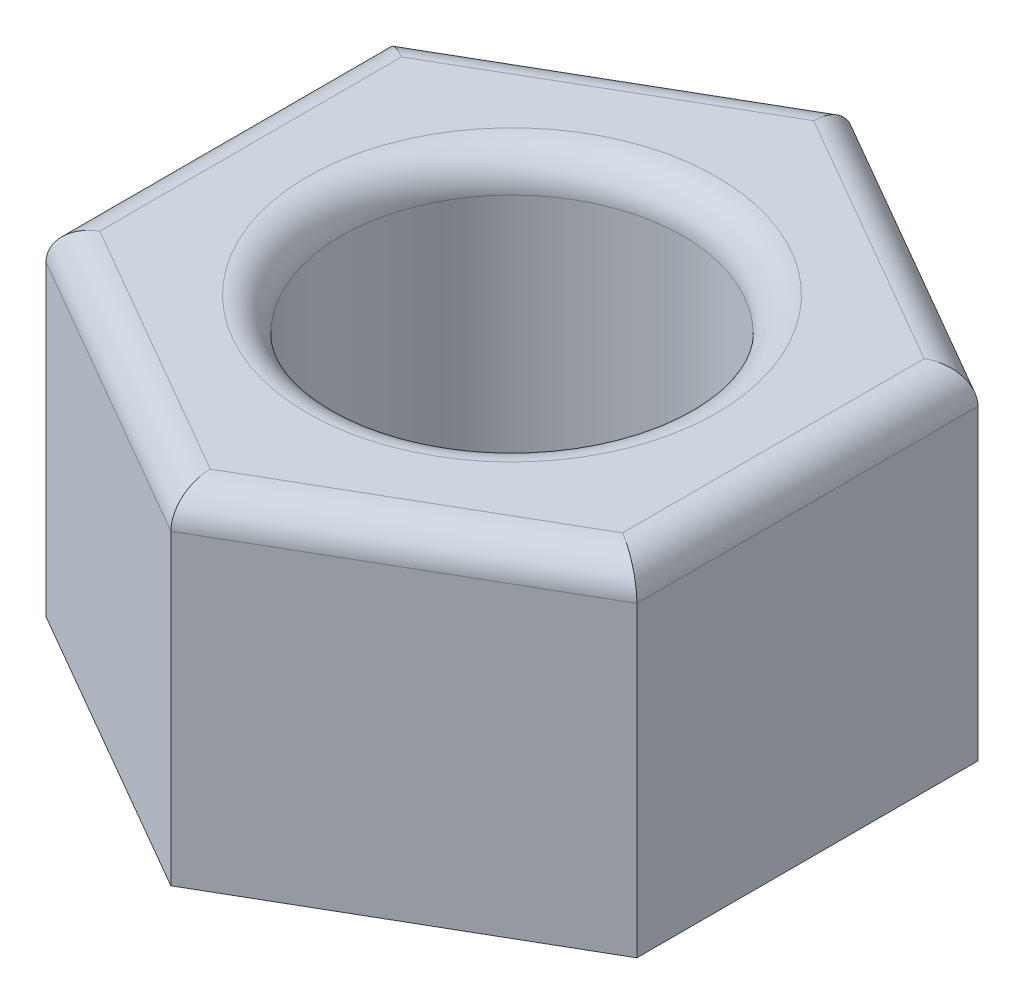
SolidWorks part; units mm, degrees
ref_plane "Front Plane" through (0, 0, 0) normal (0, 0, 1) x (1, 0, 0)
ref_plane "Top Plane" through (0, 0, 0) normal (0, 1, 0) x (1, 0, 0)
ref_plane "Right Plane" through (0, 0, 0) normal (1, 0, 0) x (0, 0, -1)
sketch "Sketch1" plane through (0, 0, 0) normal (0, 1, 0) x (1, 0, 0)
  line L1 (0, 5) -> (-4.3301, 2.5)
  line L2 (-4.3301, 2.5) -> (-4.3301, -2.5)
  line L3 (-4.3301, -2.5) -> (0, -5)
  line L4 (0, -5) -> (4.3301, -2.5)
  line L5 (4.3301, -2.5) -> (4.3301, 2.5)
  line L6 (4.3301, 2.5) -> (0, 5)
  circle A0 centre (0, 0) radius 5 construction
  circle A1 centre (0, 0) radius 4.3301 construction
  circle A2 centre (0, 0) radius 2.5
  dimension "D1" = 10
  dimension "D2" = 5
extrude "Boss-Extrude1" add sketch "Sketch1" along normal blind 5
fillet "Fillet1" radius 0.5 7 edges at (0, 5, 2.5) (4.3301, 5, 0) (2.1651, 5, 3.75) (-2.1651, 5, 3.75) (-4.3301, 5, 0) (-2.1651, 5, -3.75) (2.1651, 5, -3.75)
